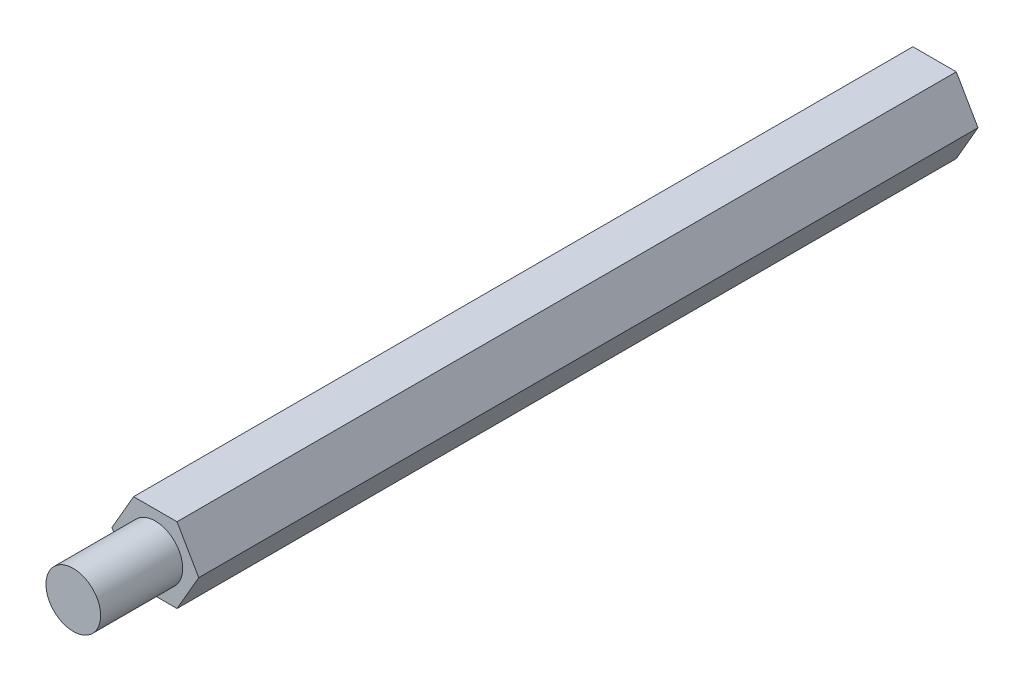
SolidWorks part; units mm, degrees
ref_plane "前视基准面" through (0, 0, 0) normal (0, 0, 1) x (1, 0, 0)
ref_plane "上视基准面" through (0, 0, 0) normal (0, 1, 0) x (1, 0, 0)
ref_plane "右视基准面" through (0, 0, 0) normal (1, 0, 0) x (0, 0, -1)
sketch "草图1" plane through (0, 0, 0) normal (0, 0, 1) x (1, 0, 0)
  line L0 (-28.6627, 0) -> (33.6774, 0) construction
  line L1 (1.5877, -2.75) -> (3.1754, 0)
  line L2 (3.1754, 0) -> (1.5877, 2.75)
  line L3 (1.5877, 2.75) -> (-1.5877, 2.75)
  line L4 (-1.5877, 2.75) -> (-3.1754, 0)
  line L5 (-3.1754, 0) -> (-1.5877, -2.75)
  line L6 (-1.5877, -2.75) -> (1.5877, -2.75)
  circle A0 centre (0, 0) radius 2.75 construction
  dimension "D1" = 5.5
extrude "拉伸1" add sketch "草图1" along normal blind 57
sketch "草图2" plane through (0, 0, 57) normal (0, 0, 1) x (1, 0, 0)
  circle A0 centre (0, 0) radius 2
  dimension "D1" = 4
extrude "拉伸2" add sketch "草图2" along normal blind 6
sketch "草图6" plane through (0, 0, 0) normal (0, 0, -1) x (-1, 0, 0)
  circle A0 centre (0, 0) radius 1.5
  dimension "D1" = 3
extrude "切除-拉伸1" cut sketch "草图6" against normal blind 5
